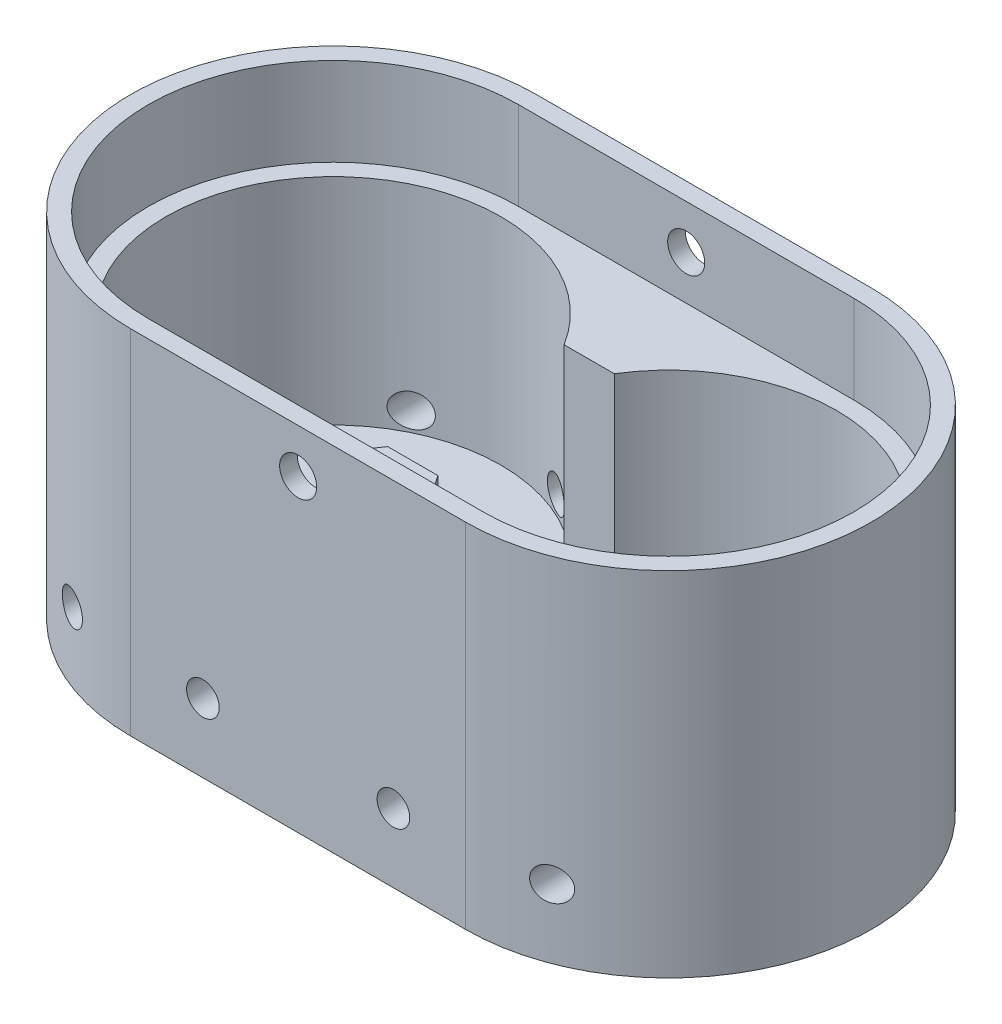
SolidWorks part; units mm, degrees
ref_plane "Front" through (0, 0, 0) normal (0, 0, 1) x (1, 0, 0)
ref_plane "Top" through (0, 0, 0) normal (0, 1, 0) x (1, 0, 0)
ref_plane "Right" through (0, 0, 0) normal (1, 0, 0) x (0, 0, -1)
sketch "Sketch1" plane through (0, 0, 0) normal (0, 1, 0) x (1, 0, 0)
  line L0 (-9.5, 11.5) -> (9.5, 11.5)
  line L1 (-9.5, -11.5) -> (9.5, -11.5)
  arc A0 (-9.5, 11.5) -> (-9.5, -11.5) centre (-9.5, 0) ccw
  arc A1 (9.5, -11.5) -> (9.5, 11.5) centre (9.5, 0) ccw
  circle A2 centre (-9.5, 0) radius 9.5 construction
  circle A3 centre (9.5, 0) radius 9.5 construction
  dimension "D1" = 2
  dimension "D2" = 19
extrude "Boss-Extrude1" add sketch "Sketch1" along normal blind 2
sketch "Sketch2" plane through (0, 2, 0) normal (0, 1, 0) x (1, 0, 0)
  line L2 (-9.5, -11.5) -> (9.5, -11.5)
  line L3 (9.5, 11.5) -> (-9.5, 11.5)
  line L4 (-9.5, -11.5) -> (9.5, -11.5)
  line L5 (9.5, 11.5) -> (-9.5, 11.5)
  line L6 (9.5, 9.5) -> (-9.5, 9.5) construction
  line L7 (-9.5, -9.5) -> (9.5, -9.5) construction
  line L9 (-1.4223, 5) -> (1.4223, 5)
  line L11 (-1.4223, -5) -> (1.4223, -5)
  arc A0 (9.5, -9.5) -> (9.5, 9.5) centre (9.5, 0) ccw
  arc A1 (-9.5, 9.5) -> (-9.5, -9.5) centre (-9.5, 0) ccw
  arc A2 (-9.5, 11.5) -> (-9.5, -11.5) centre (-9.5, 0) ccw
  arc A3 (9.5, -11.5) -> (9.5, 11.5) centre (9.5, 0) ccw
  arc A4 (-9.5, 11.5) -> (-9.5, -11.5) centre (-9.5, 0) ccw
  arc A5 (9.5, -11.5) -> (9.5, 11.5) centre (9.5, 0) ccw
  arc A6 (-1.4223, 5) -> (-1.4223, -5) centre (-9.5, 0) ccw
  arc A7 (1.4223, -5) -> (1.4223, 5) centre (9.5, 0) ccw
  point P20 (0, 5)
  point P22 (0, -5)
  arc M5 (-9.5, 11.5) -> (-9.5, -11.5) centre (-9.5, 0) ccw
  line M6 (-9.5, -11.5) -> (9.5, -11.5)
  arc M7 (9.5, -11.5) -> (9.5, 11.5) centre (9.5, 0) ccw
  line M8 (9.5, 11.5) -> (-9.5, 11.5)
  dimension "D3" = 10
  dimension "D1" = 0
  dimension "D2" = 2
extrude "Boss-Extrude2" add sketch "Sketch2" along normal blind 13 contours A7 A0 L11 A6 A1 L9 M8 M5 M6 M7
sketch "Sketch4" plane through (0, 15, 0) normal (0, 1, 0) x (1, 0, 0)
  line L0 (9.5, 10.5) -> (-9.5, 10.5)
  line L1 (-9.5, -10.5) -> (9.5, -10.5)
  line L2 (9.5, 11.5) -> (-9.5, 11.5)
  line L3 (-9.5, -11.5) -> (9.5, -11.5)
  line L4 (9.5, 11.5) -> (-9.5, 11.5)
  line L5 (-9.5, -11.5) -> (9.5, -11.5)
  arc A0 (-9.5, 10.5) -> (-9.5, -10.5) centre (-9.5, 0) ccw
  arc A1 (9.5, -10.5) -> (9.5, 10.5) centre (9.5, 0) ccw
  arc A2 (-9.5, 11.5) -> (-9.5, -11.5) centre (-9.5, 0) ccw
  arc A3 (9.5, -11.5) -> (9.5, 11.5) centre (9.5, 0) ccw
  arc A4 (-9.5, 11.5) -> (-9.5, -11.5) centre (-9.5, 0) ccw
  arc A5 (9.5, -11.5) -> (9.5, 11.5) centre (9.5, 0) ccw
  dimension "D1" = 0
  dimension "D2" = 1
extrude "Boss-Extrude3" add sketch "Sketch4" along normal blind 5
sketch "Sketch8" plane through (0, 2, 0) normal (0, 1, 0) x (1, 0, 0)
  line L0 (0, -50) -> (0, 50) construction
  circle A1 centre (-9.5, 0) radius 1.5
  arc A2 (-1.4223, 5) -> (-1.4223, -5) centre (-9.5, 0) ccw construction
  circle A3 centre (9.5, 0) radius 1.5
  dimension "D1" = 3
extrude "Cut-Extrude3" cut sketch "Sketch8" against normal through all
sketch "Sketch10" plane through (0, 2, 0) normal (0, 1, 0) x (1, 0, 0)
  line L0 (0, -50) -> (0, 50) construction
  line L1 (-15.6, 6.1) -> (-3.4, 6.1)
  line L2 (1.4223, 5) -> (-1.4223, 5)
  line L3 (-1.4223, -5) -> (1.4223, -5)
  line L4 (1.4223, 5) -> (-1.4223, 5)
  line L5 (-1.4223, -5) -> (1.4223, -5)
  line L6 (-15.6, 6.1) -> (-15.6, -6.1)
  line L7 (-15.6, -6.1) -> (-3.4, -6.1)
  line L8 (-3.4, 6.1) -> (-3.4, -6.1)
  line L9 (-15.6, 6.1) -> (-3.4, -6.1) construction
  line L10 (-15.6, -6.1) -> (-3.4, 6.1) construction
  line L11 (15.6, -6.1) -> (3.4, 6.1) construction
  line L12 (15.6, 6.1) -> (3.4, -6.1) construction
  line L13 (3.4, 6.1) -> (3.4, -6.1)
  line L14 (15.6, -6.1) -> (3.4, -6.1)
  line L15 (15.6, 6.1) -> (15.6, -6.1)
  line L16 (15.6, 6.1) -> (3.4, 6.1)
  arc A0 (1.4223, 5) -> (1.4223, -5) centre (9.5, 0) cw
  arc A2 (1.4223, -5) -> (1.4223, 5) centre (9.5, 0) ccw
  arc A3 (-1.4223, 5) -> (-1.4223, -5) centre (-9.5, 0) ccw
  arc A4 (1.4223, -5) -> (1.4223, 5) centre (9.5, 0) ccw
  arc A5 (-1.4223, 5) -> (-1.4223, -5) centre (-9.5, 0) ccw
  arc M9 (1.4223, -5) -> (1.4223, 5) centre (9.5, 0) ccw
  line M10 (1.4223, 5) -> (-1.4223, 5)
  arc M11 (-1.4223, 5) -> (-1.4223, -5) centre (-9.5, 0) ccw
  line M12 (-1.4223, -5) -> (1.4223, -5)
  dimension "D2" = 12.2
  dimension "D1" = 0
extrude "Boss-Extrude4" add sketch "Sketch10" along normal blind 0.8 contours L16 L15 L14 L13 L1 L8 L7 L6 M12 M9 M10 M11
sketch "Sketch11" plane through (0, 0, 11.5) normal (0, 0, 1) x (1, 0, 0)
  line L0 (-9.5, 0) -> (9.5, 0) construction
  line L1 (-3.4, 2.8) -> (-3.4, 2) construction
  line L2 (-9.5, 20) -> (-9.5, 0) construction
  line L3 (0, -50) -> (0, 50) construction
  circle A0 centre (-5.4, 3.9) radius 0.925
  circle A1 centre (-13.6, 3.9) radius 0.925
  circle A2 centre (13.6, 3.9) radius 0.925
  circle A3 centre (5.4, 3.9) radius 0.925
  dimension "D1" = 1.85
  dimension "D2" = 3.9
  dimension "D3" = 2
extrude "Cut-Extrude4" cut sketch "Sketch11" against normal through all
sketch "Sketch12" plane through (0, 0, 11.5) normal (0, 0, 1) x (1, 0, 0)
  line L1 (-9.5, 20) -> (-9.5, 15) construction
  circle A0 centre (0, 17.5) radius 1.05
  point P6 (-9.5, 17.5)
  dimension "D1" = 2.1
extrude "Cut-Extrude5" cut sketch "Sketch12" against normal through all
